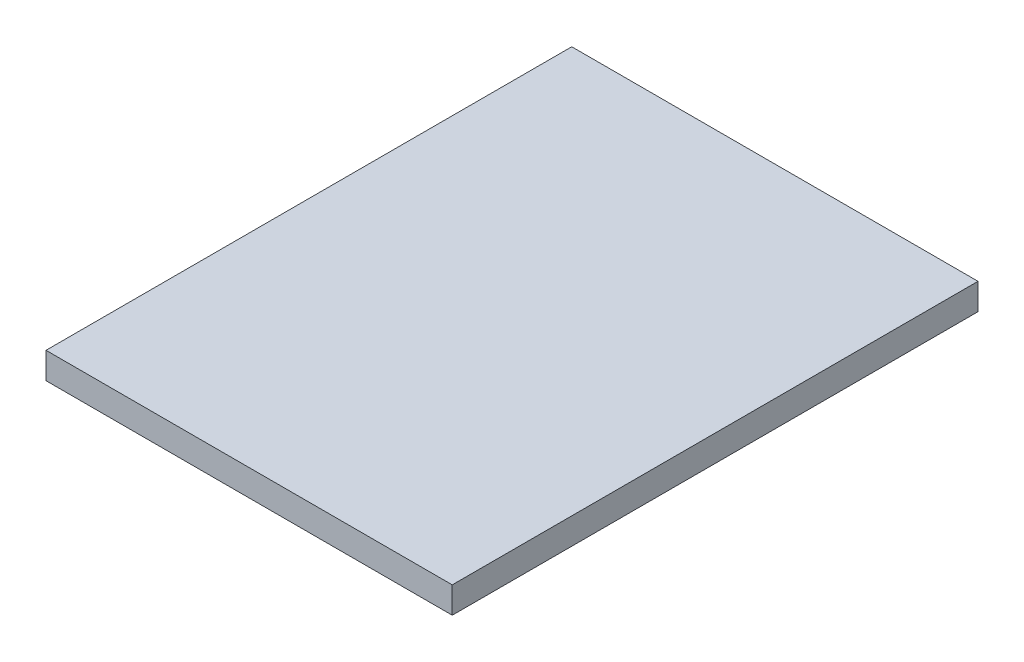
SolidWorks part; units mm, degrees
ref_plane "Front Plane" through (0, 0, 0) normal (0, 0, 1) x (1, 0, 0)
ref_plane "Top Plane" through (0, 0, 0) normal (0, 1, 0) x (1, 0, 0)
ref_plane "Right Plane" through (0, 0, 0) normal (1, 0, 0) x (0, 0, -1)
other "Configuration Table"
sketch "Sketch1" plane through (0, 0, 0) normal (0, 0, 1) x (1, 0, 0)
  line L1 (41.5, 201.5) -> (658.5, 201.5)
  line L2 (41.5, 201.5) -> (41.5, 241.5)
  line L3 (41.5, 241.5) -> (658.5, 241.5)
  line L4 (658.5, 201.5) -> (658.5, 241.5)
extrude "TOPPING_pu_alt_1" add sketch "Sketch1" against normal blind 798.5 separate body
